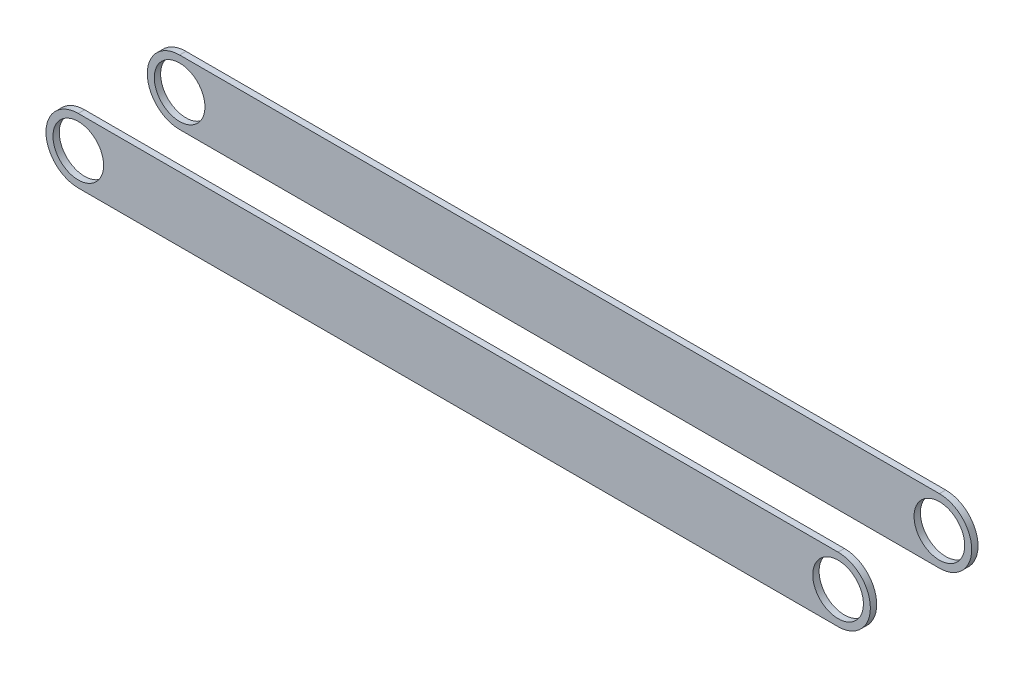
SolidWorks part; units mm, degrees
ref_plane "Front Plane" through (0, 0, 0) normal (0, 0, 1) x (1, 0, 0)
ref_plane "Top Plane" through (0, 0, 0) normal (0, 1, 0) x (1, 0, 0)
ref_plane "Right Plane" through (0, 0, 0) normal (1, 0, 0) x (0, 0, -1)
sketch "Sketch1" plane through (0, 0, 0) normal (0, 0, 1) x (1, 0, 0)
  line L0 (0, 0) -> (-1200, 0) construction
  line L1 (0, -51) -> (-1200, -51)
  line L2 (0, 51) -> (-1200, 51)
  line L3 (-601.0662, 0) -> (-957.0822, 0)
  arc A0 (0, -51) -> (0, 51) centre (0, 0) ccw
  arc A1 (-1200, 51) -> (-1200, -51) centre (-1200, 0) ccw
  circle A2 centre (0, 0) radius 40
  circle A3 centre (-1200, 0) radius 40
  point P3 (-600, 0)
  dimension "D1" = 51
  dimension "D3" = 80
  dimension "D4" = 80
  dimension "D2" = 1200
  dimension "D5" = 0
extrude "Boss-Extrude1" add sketch "Sketch1" along normal blind 10
ref_plane "Plane12" through (0, 0, 85) normal (0, 0, 1) x (1, 0, 0)
mirror "镜向4" about plane through (0, 0, 85) normal (0, 0, 1) of bodies 101
equation "\"113.8.00mm\"=200"
